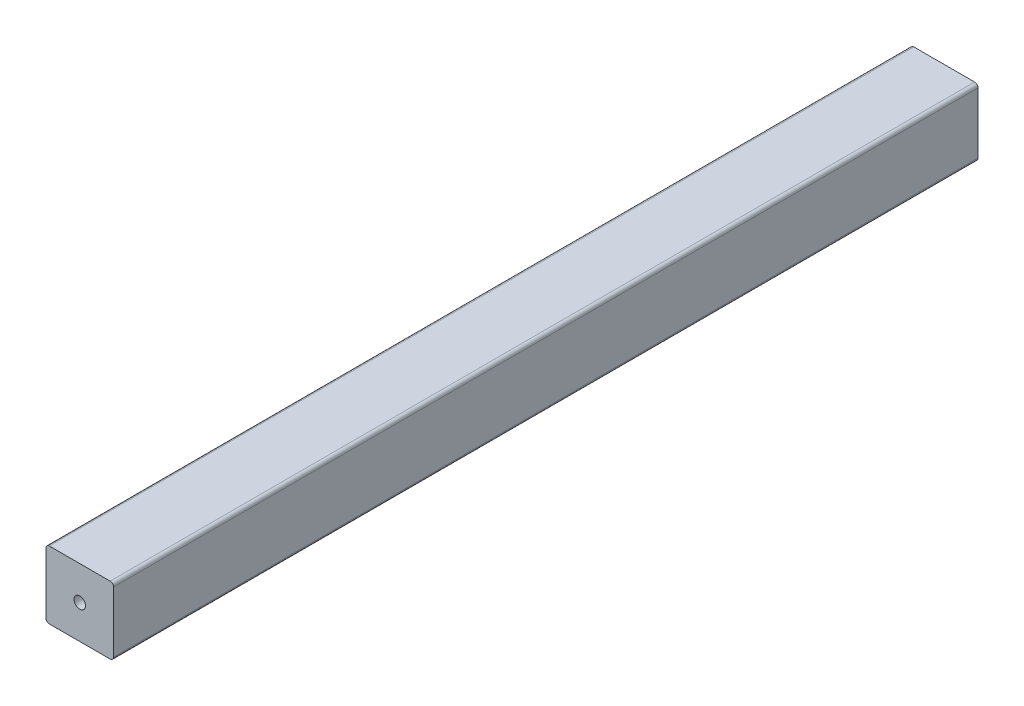
SolidWorks part; units mm, degrees
ref_plane "Front Plane" through (0, 0, 0) normal (0, 0, 1) x (1, 0, 0)
ref_plane "Top Plane" through (0, 0, 0) normal (0, 1, 0) x (1, 0, 0)
ref_plane "Right Plane" through (0, 0, 0) normal (1, 0, 0) x (0, 0, -1)
sketch "Sketch1" plane through (0, 0, 0) normal (0, 0, 1) x (1, 0, 0)
  line L1 (-20, -20) -> (20, -20)
  line L2 (-20, -20) -> (-20, 20)
  line L3 (-20, 20) -> (20, 20)
  line L4 (20, -20) -> (20, 20)
  line L5 (-20, -20) -> (20, 20) construction
  line L6 (-20, 20) -> (20, -20) construction
  circle A0 centre (0, 0) radius 2.5
  point P0 (0, 0)
  dimension "D3" = 5
  dimension "D1" = 40
  dimension "D2" = 40
extrude "Boss-Extrude1" add sketch "Sketch1" along normal mid plane 512
fillet "Fillet1" radius 2 4 edges at (20, -20, 0) (-20, -20, 0) (-20, 20, 0) (20, 20, 0)
sketch "Sketch2" plane through (0, 20, 0) normal (0, 1, 0) x (1, 0, 0)
  line L0 (0, 958.3172) -> (0, -945.7078) construction
  line L2 (18, 256) -> (-18, 256) construction
  line L3 (18, -256) -> (-18, -256) construction
  point P3 (0, -344)
  point P4 (0, 344)
  dimension "D1" = 600
  dimension "D2" = 600
hole_wizard "Ø4.5 (4.5) Diameter Hole1" positions "Sketch3" profile "Sketch4" hole size "Ø4.5" standard "ISO"
sketch "Sketch3" plane through (0, 20, 0) normal (0, 1, 0) x (1, 0, 0)
  point P0 (0, -300)
  point P3 (0, 300)
sketch "Sketch4" plane through (0, 20, 300) normal (1, 0, 0) x (0, 0, 1)
  line L0 (0, 0) -> (0, 40)
  line L1 (0, 40) -> (2.25, 40)
  line L2 (2.25, 40) -> (2.25, 0)
  line L5 (2.25, 0) -> (0, 0)
  line L11 (0, -6.35) -> (0, 107.95) construction
  dimension "Thru Hole Dia." = 4.5
  dimension "Thru Hole Depth" = 40
sketch "Sketch5" plane through (0, -20, 0) normal (0, -1, 0) x (1, 0, 0)
  line L0 (0, 256) -> (0, -1000.0028) construction
  line L1 (-18, 256) -> (18, 256) construction
  point P5 (0, 500)
  point P6 (0, 0)
  point P7 (0, -500)
  dimension "D1" = 500
  dimension "D2" = 500
hole_wizard "CBORE for M8 Hex Head Bolt1" positions "Sketch6" profile "Sketch7" counterbore size "M8" standard "ANSI Metric"
sketch "Sketch6" plane through (0, -20, 0) normal (0, -1, 0) x (-1, 0, 0)
  point P0 (0, 500)
  point P3 (0, 0)
  point P6 (0, -500)
sketch "Sketch7" plane through (0, -20, -500) normal (1, 0, 0) x (0, 0, -1)
  line L0 (0, 0) -> (0, 40)
  line L1 (0, 40) -> (4.5, 40)
  line L3 (4.5, 40) -> (4.5, 12.3)
  line L4 (4.5, 12.3) -> (9.005, 12.3)
  line L5 (9.005, 12.3) -> (9.005, 0)
  line L7 (9.005, 0) -> (0, 0)
  line L11 (0, -6.35) -> (0, 107.95) construction
  dimension "Thru Hole Dia." = 9
  dimension "Thru Hole Depth" = 40
  dimension "C'Bore Dia." = 18.01
  dimension "C'Bore Depth" = 12.3
hole_wizard "M8 Tapped Hole1" positions "Sketch8" profile "Sketch9" tap size "M8" standard "ISO"
sketch "Sketch8" plane through (0, 0, 256) normal (0, 0, 1) x (1, 0, 0)
  point P0 (0, 0)
sketch "Sketch9" plane through (0, 0, 256) normal (1, 0, 0) x (0, -1, 0)
  line L0 (0, 0) -> (0, 29.7929)
  line L1 (0, 29.7929) -> (3.4, 27.75)
  line L2 (3.4, 27.75) -> (3.4, 0)
  line L5 (3.4, 0) -> (0, 0)
  line L10 (0, 29.7929) -> (-3.4, 27.75) construction
  line L11 (0, -6.35) -> (0, 107.95) construction
  dimension "Tap Drill Dia." = 6.8
  dimension "Tap Drill Depth" = 27.75
  dimension "Drill Angle" = 118
cosmetic thread "Hole Thread1" parameters "D1"=24, "D2"=8
mirror "Mirror1" about plane through (0, 0, 0) normal (0, 0, 1) of "M8 Tapped Hole1"
cosmetic thread "Hole Thread2" parameters "D1"=24, "D2"=8
